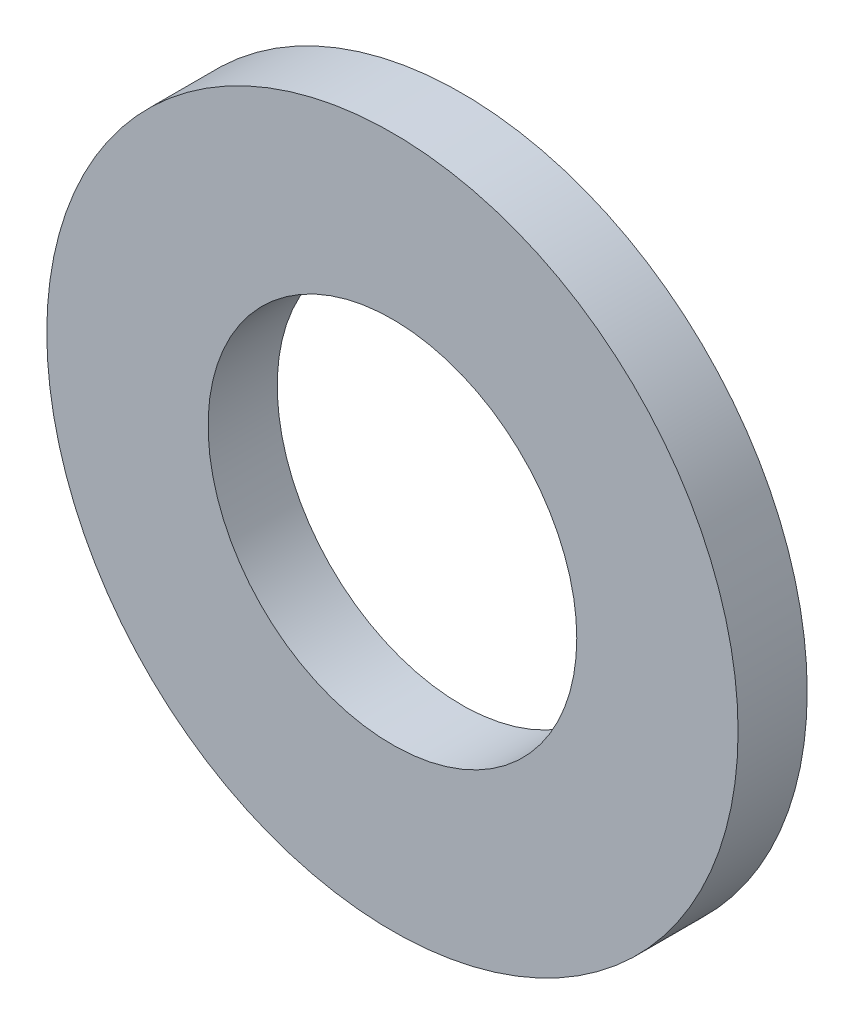
SolidWorks part; units mm, degrees
ref_plane "Front" through (0, 0, 0) normal (0, 0, 1) x (1, 0, 0)
ref_plane "Top" through (0, 0, 0) normal (0, 1, 0) x (1, 0, 0)
ref_plane "Right" through (0, 0, 0) normal (1, 0, 0) x (0, 0, -1)
sketch "Sketch1" plane through (0, 0, 0) normal (0, 0, 1) x (1, 0, 0)
  circle A0 centre (0, 0) radius 3.2
  circle A1 centre (0, 0) radius 6
  dimension "D1" = 12
  dimension "D2" = 6.4
extrude "Boss-Extrude1" add sketch "Sketch1" along normal blind 1.2
